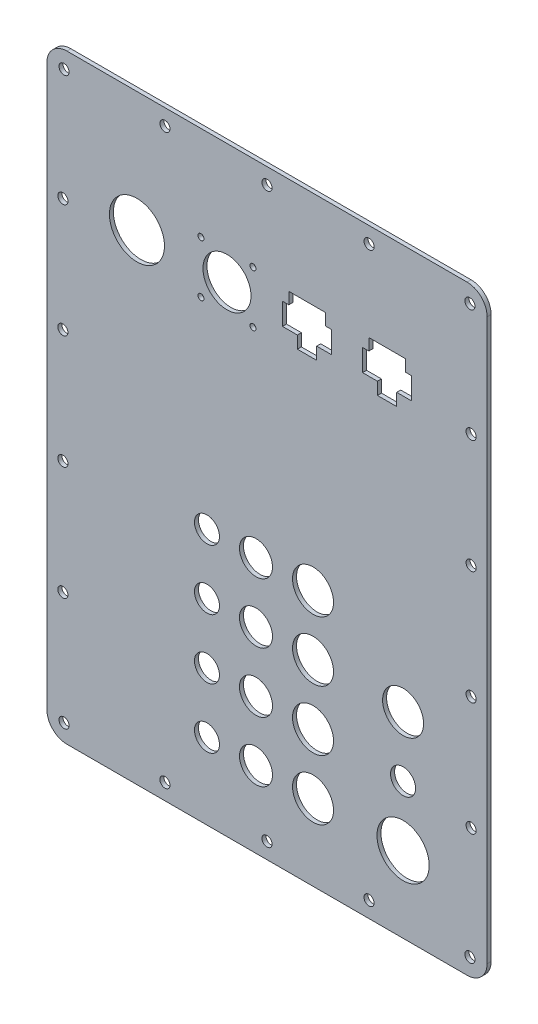
SolidWorks part; units mm, degrees
material "6061-T6 (SS)"
ref_plane "Front Plane" through (0, 0, 0) normal (0, 0, 1) x (1, 0, 0)
ref_plane "Top Plane" through (0, 0, 0) normal (0, 1, 0) x (1, 0, 0)
ref_plane "Right Plane" through (0, 0, 0) normal (1, 0, 0) x (0, 0, -1)
sketch "Sketch1" plane through (0, 0, 0) normal (0, 0, 1) x (1, 0, 0)
  line L1 (-100, -150) -> (100, -150)
  line L2 (-110, -140) -> (-110, 140)
  line L3 (-100, 150) -> (100, 150)
  line L4 (110, -140) -> (110, 140)
  line L5 (0, 150) -> (0, -150) construction
  line L6 (-110, 0) -> (110, 0) construction
  arc A0 (-100, -150) -> (-110, -140) centre (-100, -140) cw
  arc A1 (100, -150) -> (110, -140) centre (100, -140) ccw
  arc A2 (100, 150) -> (110, 140) centre (100, 140) cw
  arc A3 (-110, 140) -> (-100, 150) centre (-100, 140) cw
  point P0 (0, 0)
  point P6 (-110, -150)
  point P14 (110, 150)
  point P17 (-110, 150)
  dimension "D3" = 10
  dimension "D1" = 220
  dimension "D2" = 300
extrude "Boss-Extrude1" add sketch "Sketch1" along normal blind 2
sketch "Sketch2" plane through (0, 0, 2) normal (0, 0, 1) x (1, 0, 0)
  line L4 (0, 0) -> (0, 142) construction
  line L5 (0, 0) -> (-102, 0) construction
  line L8 (-100, -142) -> (100, -142)
  line L9 (102, -140) -> (102, 140)
  line L10 (100, 142) -> (-100, 142)
  line L11 (-102, 140) -> (-102, -140)
  line L12 (-100, -142) -> (100, -142) construction
  line L13 (102, -140) -> (102, 140) construction
  line L14 (100, 142) -> (-100, 142) construction
  line L15 (-102, 140) -> (-102, -140) construction
  circle A4 centre (-101.4142, 141.4142) radius 2.525
  circle A5 centre (101.4142, 141.4142) radius 2.525
  arc A8 (-102, -140) -> (-100, -142) centre (-100, -140) ccw
  arc A9 (100, -142) -> (102, -140) centre (100, -140) ccw
  arc A10 (102, 140) -> (100, 142) centre (100, 140) ccw
  arc A11 (-100, 142) -> (-102, 140) centre (-100, 140) ccw
  arc A12 (-102, -140) -> (-100, -142) centre (-100, -140) ccw construction
  arc A13 (100, -142) -> (102, -140) centre (100, -140) ccw construction
  arc A14 (102, 140) -> (100, 142) centre (100, 140) ccw construction
  arc A15 (-100, 142) -> (-102, 140) centre (-100, 140) ccw construction
  circle A16 centre (-51, 142) radius 2.525
  circle A17 centre (51, 142) radius 2.525
  circle A18 centre (-102, 85.2) radius 2.525
  circle A19 centre (-102, 28.4) radius 2.525
  circle A20 centre (102, 28.4) radius 2.525
  circle A21 centre (102, 85.2) radius 2.525
  circle A22 centre (102, -28.4) radius 2.525
  circle A23 centre (102, -85.2) radius 2.525
  circle A24 centre (101.4142, -141.4142) radius 2.525
  circle A25 centre (51, -142) radius 2.525
  circle A26 centre (-51, -142) radius 2.525
  circle A27 centre (-101.4142, -141.4142) radius 2.525
  circle A28 centre (-102, -85.2) radius 2.525
  circle A29 centre (-102, -28.4) radius 2.525
  circle A30 centre (0, 142) radius 2.525
  circle A31 centre (0, -142) radius 2.525
  dimension "D2" = 5.05
  dimension "D3" = 204
  dimension "D4" = 284
  dimension "D5" = 51
  dimension "D6" = 56.8
  dimension "D7" = 56.8
  dimension "D1" = 8
extrude "Cut-Extrude1" cut sketch "Sketch2" against normal through all
sketch "Sketch3" plane through (0, 0, 2) normal (0, 0, 1) x (1, 0, 0)
  line L0 (-100, -150) -> (100, -150) construction
  line L3 (12.75, -112) -> (2.75, -112) construction
  line L4 (-13.75, -112) -> (-23.75, -112) construction
  line L5 (-110, 140) -> (-110, -140) construction
  circle A0 centre (23, -112) radius 10.25
  circle A1 centre (-5.5, -112) radius 8.25
  circle A2 centre (23, -82) radius 10.25
  circle A3 centre (-5.5, -82) radius 8.25
  circle A4 centre (23, -52) radius 10.25
  circle A5 centre (-5.5, -52) radius 8.25
  circle A6 centre (23, -22) radius 10.25
  circle A7 centre (-5.5, -22) radius 8.25
  circle A8 centre (-30, -112) radius 6.25
  circle A9 centre (-30, -82) radius 6.25
  circle A10 centre (-30, -52) radius 6.25
  circle A11 centre (-30, -22) radius 6.25
  dimension "D1" = 20.5
  dimension "D2" = 38
  dimension "D4" = 16.5
  dimension "D5" = 10
  dimension "D7" = 30
  dimension "D3" = 80
  dimension "D8" = 12.5
  dimension "D6" = 4
extrude "Cut-Extrude2" cut sketch "Sketch3" against normal through all
sketch "Sketch5" plane through (0, 0, 2) normal (0, 0, 1) x (1, 0, 0)
  line L2 (-100, -150) -> (100, -150) construction
  line L3 (-110, 140) -> (-110, -140) construction
  point P1 (20, 90)
  line B0 (10.875, 101.45) -> (10.875, 95.6)
  line B1 (20, 101.45) -> (20, 78.55) construction
  line B2 (32.25, 95.6) -> (32.25, 84.7)
  line B3 (29.125, 95.6) -> (32.25, 95.6)
  line B4 (29.125, 101.45) -> (29.125, 95.6)
  line B5 (7.75, 84.7) -> (15.175, 84.7)
  line B6 (15.175, 84.7) -> (15.175, 78.55)
  line B7 (15.175, 78.55) -> (24.825, 78.55)
  line B8 (24.825, 78.55) -> (24.825, 84.7)
  line B9 (24.825, 84.7) -> (32.25, 84.7)
  line B10 (29.125, 101.45) -> (10.875, 101.45)
  line B11 (10.875, 95.6) -> (7.75, 95.6)
  line B12 (7.75, 95.6) -> (7.75, 84.7)
  line B13 (50.875, 101.45) -> (50.875, 95.6)
  line B14 (60, 101.45) -> (60, 78.55) construction
  line B15 (72.25, 95.6) -> (72.25, 84.7)
  line B16 (69.125, 95.6) -> (72.25, 95.6)
  line B17 (69.125, 101.45) -> (69.125, 95.6)
  line B18 (47.75, 84.7) -> (55.175, 84.7)
  line B19 (55.175, 84.7) -> (55.175, 78.55)
  line B20 (55.175, 78.55) -> (64.825, 78.55)
  line B21 (64.825, 78.55) -> (64.825, 84.7)
  line B22 (64.825, 84.7) -> (72.25, 84.7)
  line B23 (69.125, 101.45) -> (50.875, 101.45)
  line B24 (50.875, 95.6) -> (47.75, 95.6)
  line B25 (47.75, 95.6) -> (47.75, 84.7)
  dimension "D1" = 40
  dimension "D2" = 240
  dimension "D3" = 130
sketch_block_instance "Female US 3 Pin Power Socket Plug Panel Mount-1"
sketch_block "Block1" parameters "D1"=24.5
sketch_block_instance "Block1-1"
extrude "Cut-Extrude3" cut sketch "Sketch5" against normal through all
sketch "Sketch6" plane through (0, 0, 2) normal (0, 0, 1) x (1, 0, 0)
  line L0 (-110, 140) -> (-110, -140) construction
  line L1 (-100, -150) -> (100, -150) construction
  line L2 (-20, 90) -> (-20, 102) construction
  line L3 (-20, 90) -> (-8, 90) construction
  circle A0 centre (-20, 90) radius 12
  circle A1 centre (-7, 103) radius 1.5
  circle A2 centre (-33, 103) radius 1.5
  circle A3 centre (-7, 77) radius 1.5
  circle A4 centre (-33, 77) radius 1.5
  dimension "D1" = 24
  dimension "D2" = 90
  dimension "D3" = 240
  dimension "D4" = 3
  dimension "D5" = 26
  dimension "D6" = 26
extrude "Cut-Extrude4" cut sketch "Sketch6" against normal through all
sketch "Sketch7" plane through (0, 0, 2) normal (0, 0, 1) x (1, 0, 0)
  line L0 (-20, 90) -> (-65, 90) construction
  circle A0 centre (-65, 90) radius 13.75
  dimension "D1" = 27.5
  dimension "D2" = 45
extrude "Cut-Extrude5" cut sketch "Sketch7" against normal up to next
sketch "Sketch8" plane through (0, 0, 2) normal (0, 0, 1) x (1, 0, 0)
  line L0 (23, -112) -> (68, -112) construction
  circle A0 centre (68, -112) radius 13.05
  dimension "D1" = 26.1
  dimension "D2" = 45
extrude "Cut-Extrude6" cut sketch "Sketch8" against normal up to next
sketch "Sketch9" plane through (0, 0, 2) normal (0, 0, 1) x (1, 0, 0)
  line L0 (-30, -82) -> (68, -82) construction
  line L1 (68, -112) -> (68, -82) construction
  line L2 (68, -82) -> (68, -52) construction
  line L3 (23, -52) -> (68, -52) construction
  circle A0 centre (68, -52) radius 10.25
  circle A1 centre (68, -82) radius 6.25
  circle A2 centre (23, -52) radius 10.25 construction
  circle A3 centre (-30, -82) radius 6.25 construction
extrude "Cut-Extrude7" cut sketch "Sketch9" against normal up to surface (2 mm away) up to face at (54.95, -112, 0)
equation "\"D5@Sketch2\"=\"D3@Sketch2\"/4"
equation "\"D6@Sketch2\"=\"D4@Sketch2\"/5"
equation "\"D7@Sketch2\"=\"D4@Sketch2\"/5"
